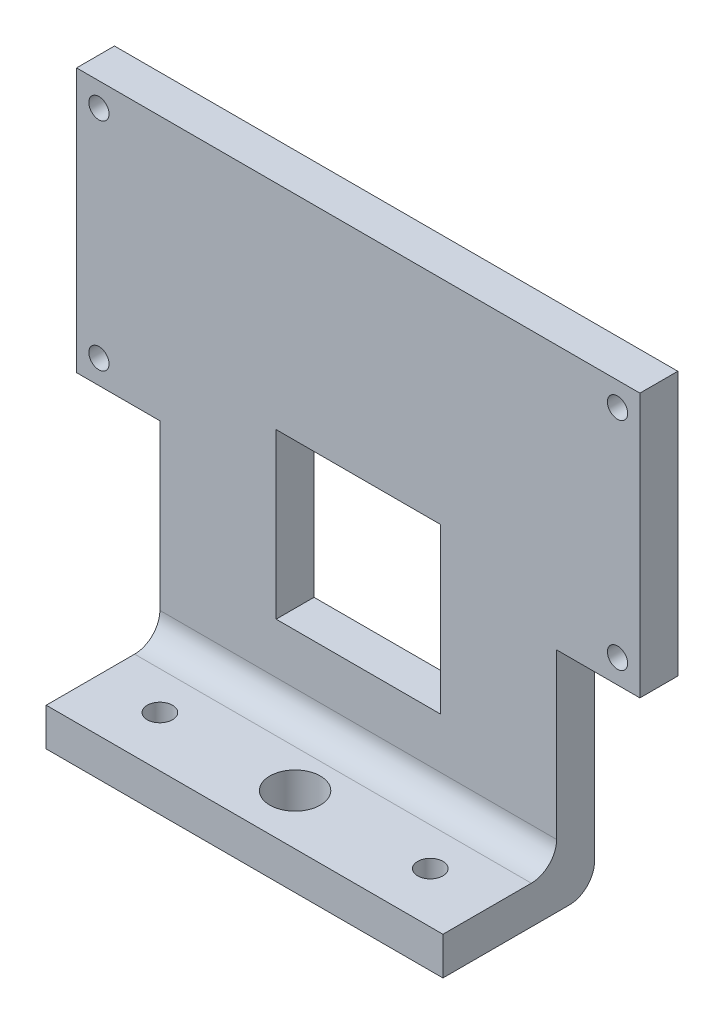
SolidWorks part; units mm, degrees
material "Acrylic (Medium-high impact)"
ref_plane "Front Plane" through (0, 0, 0) normal (0, 0, 1) x (1, 0, 0)
ref_plane "Top Plane" through (0, 0, 0) normal (0, 1, 0) x (1, 0, 0)
ref_plane "Right Plane" through (0, 0, 0) normal (1, 0, 0) x (0, 0, -1)
sketch "Sketch1" plane through (0, 0, 0) normal (0, 1, 0) x (1, 0, 0)
  line L0 (0, -3) -> (0, -5)
  line L1 (-15.705, -1) -> (-10.705, -1) construction
  line L2 (-10.705, -1) -> (0, -1) construction
  line L3 (0, 1) -> (0, 7)
  line L4 (0, 7) -> (-15.705, 7)
  line L6 (0, -5) -> (-15.705, -5)
  line L7 (-15.705, 7) -> (-15.705, -5)
  circle A0 centre (-10.705, -1) radius 1
  arc A1 (0, 1) -> (0, -3) centre (0, -1) ccw
  point P3 (0, 0)
  dimension "D5" = 2
  dimension "D6" = 2
  dimension "D1" = 12
  dimension "D2" = 5
  dimension "D3" = 10.705
  dimension "D4" = 4
extrude "Boss-Extrude1" add sketch "Sketch1" along normal blind 3
ref_plane "Plane1" through (0, 0, -7) normal (0, 0, -1) x (-1, 0, 0)
sketch "Sketch2" plane through (0, 0, -7) normal (0, 0, -1) x (-1, 0, 0)
  line L0 (15.705, 3) -> (15.705, 18)
  line L1 (0, 3) -> (0, 9) construction
  line L2 (0, 9) -> (6.5, 9)
  line L3 (6.5, 9) -> (6.5, 22)
  line L5 (15.705, 3) -> (0, 3)
  line L6 (6.5, 22) -> (0, 22)
  line L7 (22.3, 18) -> (22.3, 38.9)
  line L8 (15.705, 18) -> (22.3, 18)
  line L9 (0, 9) -> (0, 3)
  line L10 (22.3, 38.9) -> (0, 38.9)
  line L11 (0, 38.9) -> (0, 22)
  line L12 (22.3, 18) -> (20.53, 19.88) construction
  line L13 (22.3, 28.45) -> (0, 28.45) construction
  circle A0 centre (20.53, 19.88) radius 0.8
  circle A1 centre (20.53, 37.02) radius 0.8
  dimension "D11" = 1.6
  dimension "D1" = 15
  dimension "D2" = 6
  dimension "D3" = 6.5
  dimension "D4" = 13
  dimension "D5" = 15.705
  dimension "D6" = 22.3
  dimension "D7" = 20.9
  dimension "D8" = 22.3
  dimension "D9" = 1.88
  dimension "D10" = 1.77
  dimension "D12" = 2.5821
extrude "Boss-Extrude2" add sketch "Sketch2" against normal blind 3
mirror "Mirror1" about plane through (0, 0, 0) normal (1, 0, 0) of "Boss-Extrude1", "Boss-Extrude2"
fillet "Fillet1" radius 2 2 edges at (0, 3, -4) (0, 0, -7)
